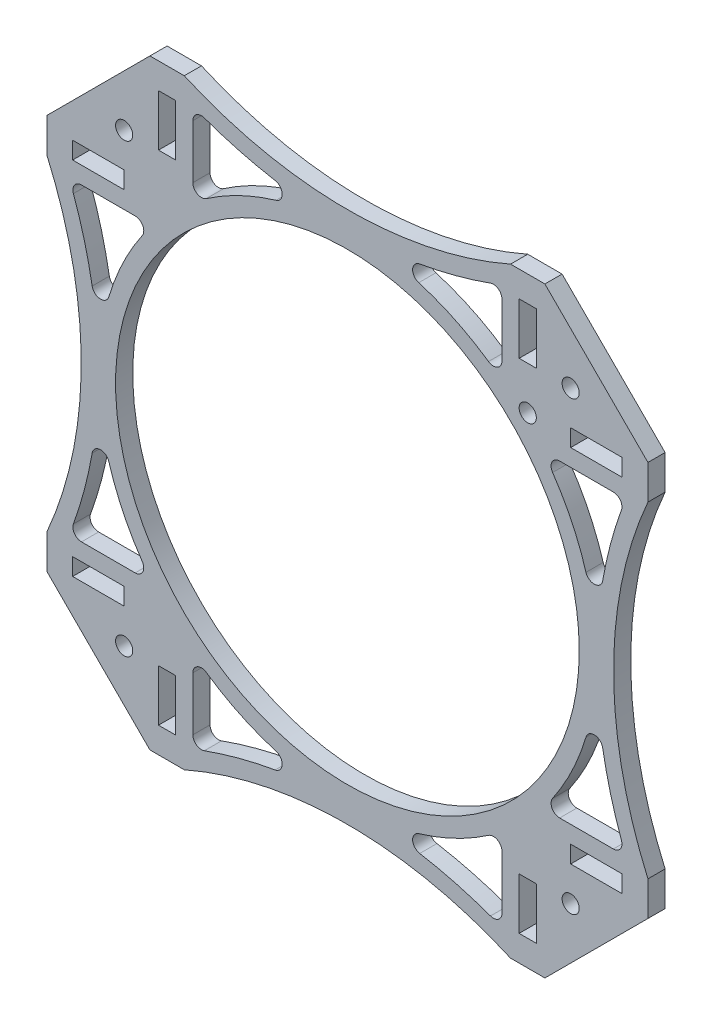
SolidWorks part; units mm, degrees
ref_plane "Front Plane" through (0, 0, 0) normal (0, 0, 1) x (1, 0, 0)
ref_plane "Top Plane" through (0, 0, 0) normal (0, 1, 0) x (1, 0, 0)
ref_plane "Right Plane" through (0, 0, 0) normal (1, 0, 0) x (0, 0, -1)
sketch "Sketch1" plane through (0, 0, 0) normal (0, 0, 1) x (1, 0, 0)
  line L0 (0, 60) -> (0, 0) construction
  line L1 (0, 0) -> (69.8899, 0) construction
  line L2 (0, 0) -> (53.7008, 53.7008) construction
  line L3 (23, 35) -> (35, 23)
  line L4 (-23, 35) -> (-19, 35)
  line L5 (-35, 23) -> (-35, 19)
  line L6 (-23, -35) -> (-19, -35)
  line L7 (35, 23) -> (35, 19)
  line L8 (35, -23) -> (23, -35)
  line L9 (-23, -35) -> (-35, -23)
  line L10 (-35, 23) -> (-23, 35)
  line L11 (19, 35) -> (23, 35)
  line L12 (-35, -19) -> (-35, -23)
  line L13 (35, -19) -> (35, -23)
  line L14 (19, -35) -> (23, -35)
  line L15 (18, 30.9708) -> (18, 24.7184)
  line L16 (-18, 30.9708) -> (-18, 24.7184)
  line L17 (-20, 26) -> (-22, 26)
  line L18 (20, 32) -> (22, 32)
  line L19 (20, 32) -> (20, 26)
  line L20 (20, 26) -> (22, 26)
  line L21 (22, 32) -> (22, 26)
  line L22 (-20, 32) -> (-22, 32)
  line L23 (-22, 32) -> (-22, 26)
  line L24 (-20, 32) -> (-20, 26)
  line L25 (32, 22) -> (26, 22)
  line L26 (32, 20) -> (32, 22)
  line L27 (32, 20) -> (26, 20)
  line L28 (26, 20) -> (26, 22)
  line L29 (26, -20) -> (26, -22)
  line L30 (32, -20) -> (26, -20)
  line L31 (32, -20) -> (32, -22)
  line L32 (32, -22) -> (26, -22)
  line L33 (30.9708, 18) -> (24.7184, 18)
  line L34 (30.9708, -18) -> (24.7184, -18)
  line L35 (22, -32) -> (22, -26)
  line L36 (20, -32) -> (22, -32)
  line L37 (20, -32) -> (20, -26)
  line L38 (20, -26) -> (22, -26)
  line L39 (-20, -26) -> (-22, -26)
  line L40 (-20, -32) -> (-20, -26)
  line L41 (-20, -32) -> (-22, -32)
  line L42 (-22, -32) -> (-22, -26)
  line L43 (18, -30.9708) -> (18, -24.7184)
  line L44 (-18, -30.9708) -> (-18, -24.7184)
  line L45 (-32, -22) -> (-26, -22)
  line L46 (-32, -20) -> (-32, -22)
  line L47 (-32, -20) -> (-26, -20)
  line L48 (-26, -20) -> (-26, -22)
  line L49 (-26, 20) -> (-26, 22)
  line L50 (-32, 20) -> (-26, 20)
  line L51 (-32, 20) -> (-32, 22)
  line L52 (-32, 22) -> (-26, 22)
  line L53 (-30.9708, -18) -> (-24.7184, -18)
  line L54 (-30.9708, 18) -> (-24.7184, 18)
  circle A0 centre (0, 0) radius 27
  arc A1 (-19, 35) -> (19, 35) centre (0, 78.125) ccw
  arc A2 (35, 19) -> (35, -19) centre (78.125, 0) ccw
  arc A3 (19, -35) -> (-19, -35) centre (0, -78.125) ccw
  arc A4 (-35, -19) -> (-35, 19) centre (-78.125, 0) ccw
  circle A5 centre (26, 26) radius 1
  circle A6 centre (21, 21) radius 1
  arc A7 (-8.3085, 27.7843) -> (-8.4236, 29.7276) centre (-8.595, 28.7424) ccw
  arc A8 (-16.6608, 31.9116) -> (-8.4236, 29.7276) centre (0, 78.125) ccw
  arc A9 (16.4333, 23.8945) -> (8.3085, 27.7843) centre (0, 0) ccw
  arc A10 (-19.8064, 33.1698) -> (19.8064, 33.1698) centre (0, 78.125) ccw construction
  arc A11 (8.3085, 27.7843) -> (8.4236, 29.7276) centre (8.595, 28.7424) cw
  arc A12 (8.4236, 29.7276) -> (16.6608, 31.9116) centre (0, 78.125) ccw
  arc A13 (-8.3085, 27.7843) -> (-16.4333, 23.8945) centre (0, 0) ccw
  arc A14 (16.4333, 23.8945) -> (18, 24.7184) centre (17, 24.7184) ccw
  arc A15 (16.6608, 31.9116) -> (18, 30.9708) centre (17, 30.9708) cw
  arc A16 (-18, 24.7184) -> (-16.4333, 23.8945) centre (-17, 24.7184) ccw
  arc A17 (-16.6608, 31.9116) -> (-18, 30.9708) centre (-17, 30.9708) ccw
  circle A18 centre (26, -26) radius 1
  arc A20 (27.7843, 8.3085) -> (23.8945, 16.4333) centre (0, 0) ccw
  arc A21 (24.7184, 18) -> (23.8945, 16.4333) centre (24.7184, 17) ccw
  arc A22 (31.9116, 16.6608) -> (30.9708, 18) centre (30.9708, 17) ccw
  arc A23 (31.9116, 16.6608) -> (29.7276, 8.4236) centre (78.125, 0) ccw
  arc A24 (27.7843, 8.3085) -> (29.7276, 8.4236) centre (28.7424, 8.595) ccw
  arc A25 (27.7843, -8.3085) -> (29.7276, -8.4236) centre (28.7424, -8.595) cw
  arc A26 (29.7276, -8.4236) -> (31.9116, -16.6608) centre (78.125, 0) ccw
  arc A27 (23.8945, -16.4333) -> (27.7843, -8.3085) centre (0, 0) ccw
  arc A28 (23.8945, -16.4333) -> (24.7184, -18) centre (24.7184, -17) ccw
  arc A29 (31.9116, -16.6608) -> (30.9708, -18) centre (30.9708, -17) cw
  circle A30 centre (-26, -26) radius 1
  arc A32 (8.3085, -27.7843) -> (16.4333, -23.8945) centre (0, 0) ccw
  arc A33 (18, -24.7184) -> (16.4333, -23.8945) centre (17, -24.7184) ccw
  arc A34 (16.6608, -31.9116) -> (18, -30.9708) centre (17, -30.9708) ccw
  arc A35 (16.6608, -31.9116) -> (8.4236, -29.7276) centre (0, -78.125) ccw
  arc A36 (8.3085, -27.7843) -> (8.4236, -29.7276) centre (8.595, -28.7424) ccw
  arc A37 (-8.3085, -27.7843) -> (-8.4236, -29.7276) centre (-8.595, -28.7424) cw
  arc A38 (-8.4236, -29.7276) -> (-16.6608, -31.9116) centre (0, -78.125) ccw
  arc A39 (-16.4333, -23.8945) -> (-8.3085, -27.7843) centre (0, 0) ccw
  arc A40 (-16.4333, -23.8945) -> (-18, -24.7184) centre (-17, -24.7184) ccw
  arc A41 (-16.6608, -31.9116) -> (-18, -30.9708) centre (-17, -30.9708) cw
  circle A42 centre (-26, 26) radius 1
  arc A44 (-27.7843, -8.3085) -> (-23.8945, -16.4333) centre (0, 0) ccw
  arc A45 (-24.7184, -18) -> (-23.8945, -16.4333) centre (-24.7184, -17) ccw
  arc A46 (-31.9116, -16.6608) -> (-30.9708, -18) centre (-30.9708, -17) ccw
  arc A47 (-31.9116, -16.6608) -> (-29.7276, -8.4236) centre (-78.125, 0) ccw
  arc A48 (-27.7843, -8.3085) -> (-29.7276, -8.4236) centre (-28.7424, -8.595) ccw
  arc A49 (-27.7843, 8.3085) -> (-29.7276, 8.4236) centre (-28.7424, 8.595) cw
  arc A50 (-29.7276, 8.4236) -> (-31.9116, 16.6608) centre (-78.125, 0) ccw
  arc A51 (-23.8945, 16.4333) -> (-27.7843, 8.3085) centre (0, 0) ccw
  arc A52 (-23.8945, 16.4333) -> (-24.7184, 18) centre (-24.7184, 17) ccw
  arc A53 (-31.9116, 16.6608) -> (-30.9708, 18) centre (-30.9708, 17) cw
  circle A54 centre (-21, 21) radius 1 [skipped]
  circle A55 centre (21, -21) radius 1 [skipped]
  circle A56 centre (-21, -21) radius 1 [skipped]
  point P21 (0, 0)
  point P30 (0, 0)
  point P157 (0, 0)
  dimension "D1" = 4
  dimension "D4" = 2
  dimension "D5" = 1
  dimension "D3" = 2
  dimension "D2" = 4
  dimension "D6" = 4
extrude "Boss-Extrude1" add sketch "Sketch1" along normal blind 2
